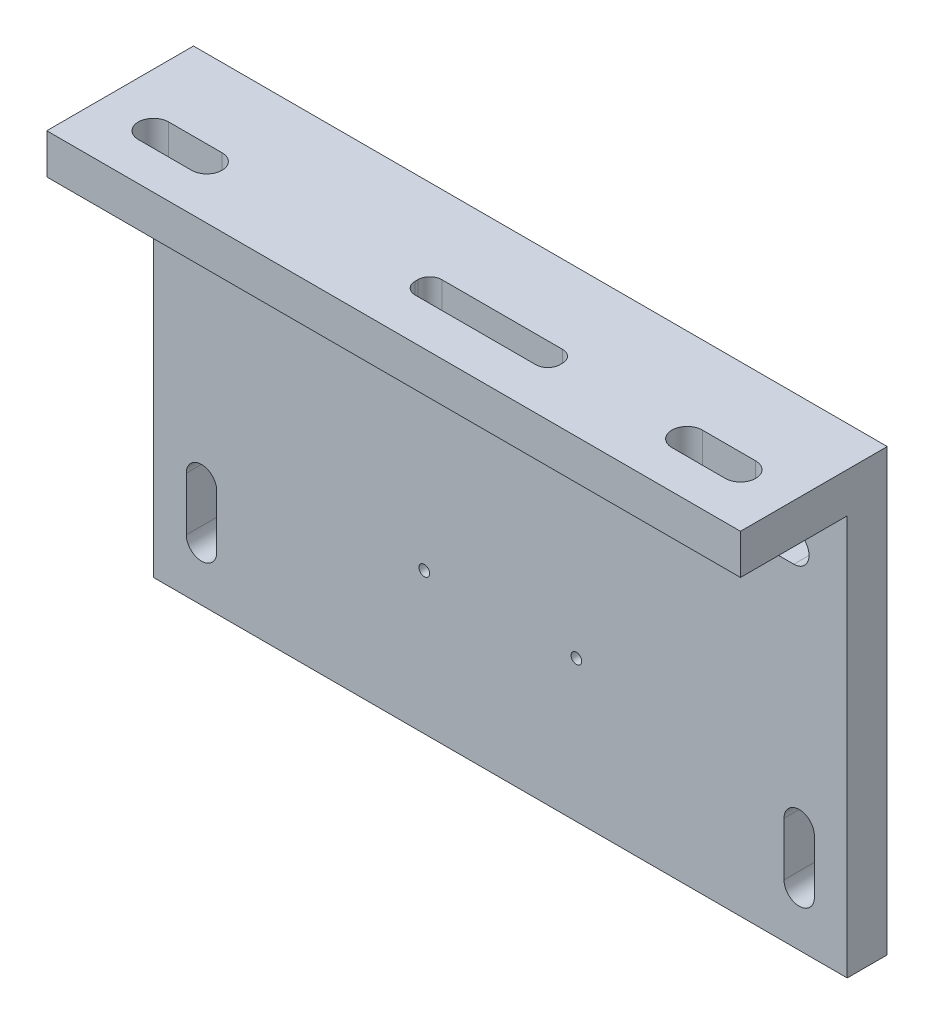
SolidWorks part; units mm, degrees
ref_plane "前视基准面" through (0, 0, 0) normal (0, 0, 1) x (1, 0, 0)
ref_plane "上视基准面" through (0, 0, 0) normal (0, 1, 0) x (1, 0, 0)
ref_plane "右视基准面" through (0, 0, 0) normal (1, 0, 0) x (0, 0, -1)
other "Configuration Table"
sketch "Skeleton" plane through (0, 0, 0) normal (0, 0, 1) x (1, 0, 0)
  line L0 (0, 170) -> (0, 0) construction
  point P0 (0, 0)
  point P1 (0, 170)
  dimension "D1" = 170
sketch "Sketch4" plane through (0, 0, 0) normal (1, 0, 0) x (0, 0, -1)
  line L1 (180, 170) -> (165, 170)
  line L2 (180, 170) -> (180, 20)
  line L3 (180, 20) -> (165, 20)
  line L4 (165, 170) -> (165, 20)
  dimension "D2" = 15
  dimension "D3" = 150
extrude "Middle" add sketch "Sketch4" along normal mid plane 260
sketch "Sketch10" plane through (0, 0, -180) normal (0, 0, -1) x (-1, 0, 0)
  line L0 (-130, 20) -> (130, 20) construction
  line L2 (0, -28.086) -> (0, 198.8498) construction
  line L3 (-130, 170) -> (130, 170) construction
  line L4 (-110, 155.7) -> (-90, 155.7)
  line L5 (-90, 144.3) -> (-110, 144.3)
  line L6 (90, 144.3) -> (110, 144.3)
  line L7 (110, 155.7) -> (90, 155.7)
  line L8 (-130, 20) -> (-130, 170) construction
  line L9 (-117.7, 60) -> (-117.7, 40)
  line L10 (-106.3, 40) -> (-106.3, 60)
  line L12 (106.3, 40) -> (106.3, 60)
  line L13 (117.7, 60) -> (117.7, 40)
  circle A0 centre (-28.5, 150) radius 2
  circle A1 centre (28.5, 150) radius 2
  circle A2 centre (28.5, 73) radius 2
  circle A3 centre (-28.5, 73) radius 2
  arc A4 (-90, 155.7) -> (-90, 144.3) centre (-90, 150) cw
  arc A5 (-110, 155.7) -> (-110, 144.3) centre (-110, 150) ccw
  arc A6 (90, 155.7) -> (90, 144.3) centre (90, 150) ccw
  arc A7 (110, 155.7) -> (110, 144.3) centre (110, 150) cw
  arc A8 (-117.7, 40) -> (-106.3, 40) centre (-112, 40) ccw
  arc A9 (-106.3, 60) -> (-117.7, 60) centre (-112, 60) ccw
  arc A10 (117.7, 40) -> (106.3, 40) centre (112, 40) cw
  arc A11 (106.3, 60) -> (117.7, 60) centre (112, 60) cw
  point P0 (-28.5, 150)
  point P1 (-28.5, 73)
  point P2 (28.5, 73)
  point P3 (28.5, 150)
  dimension "D4" = 4
  dimension "D5" = 4
  dimension "D6" = 4
  dimension "D7" = 4
  dimension "D12" = 11.4
  dimension "D1" = 77
  dimension "D2" = 77
  dimension "D3" = 57
  dimension "D8" = 20
  dimension "D9" = 11.4
  dimension "D10" = 20
  dimension "D11" = 20
  dimension "D13" = 18
  dimension "D14" = 20
  dimension "D15" = 20
extrude "Middle Holes" cut sketch "Sketch10" against normal through all
sketch "Sketch11" plane through (0, 0, 0) normal (1, 0, 0) x (0, 0, -1)
  line L1 (180, 170) -> (125, 170)
  line L2 (180, 170) -> (180, 185)
  line L3 (180, 185) -> (125, 185)
  line L4 (125, 170) -> (125, 185)
  dimension "D1" = 15
  dimension "D2" = 55
extrude "Upper" add sketch "Sketch11" along normal mid plane 260
sketch "Sketch12" plane through (0, 0, 0) normal (0, 1, 0) x (1, 0, 0)
  line L0 (-110, 139.3) -> (-90, 139.3)
  line L1 (-90, 150.7) -> (-110, 150.7)
  line L3 (130, 180) -> (-130, 180) construction
  line L4 (-130, 180) -> (-130, 125) construction
  line L5 (0, -99) -> (0, 99) construction
  line L6 (110, 139.3) -> (90, 139.3)
  line L7 (90, 150.7) -> (110, 150.7)
  arc A2 (-110, 150.7) -> (-110, 139.3) centre (-110, 145) ccw
  arc A3 (-90, 139.3) -> (-90, 150.7) centre (-90, 145) ccw
  arc A4 (90, 139.3) -> (90, 150.7) centre (90, 145) cw
  arc A5 (110, 150.7) -> (110, 139.3) centre (110, 145) cw
  dimension "D2" = 11.4
  dimension "D1" = 35
  dimension "D3" = 20
  dimension "D4" = 20
extrude "Upper Holes" cut sketch "Sketch12" against normal up to surface (15 mm away) from surface at 185 up to face at (0, 170, -145) starting at face at (0, 185, -152.5)
sketch "Sketch14" plane through (0, 185, 0) normal (0, 1, 0) x (1, 0, 0)
  line L0 (42.098, 145.2) -> (42.098, 146.2) construction
  line L1 (-7.6345, 140.7) -> (37.598, 140.7) construction
  line L15 (-12.1345, 146.2) -> (-12.1345, 145.2) construction
  line L16 (37.598, 150.7) -> (-7.6345, 150.7) construction
  line L17 (42.098, 145.2) -> (42.098, 146.2)
  line L18 (-7.6345, 140.7) -> (37.598, 140.7)
  line L19 (-12.1345, 146.2) -> (-12.1345, 145.2)
  line L20 (37.598, 150.7) -> (-7.6345, 150.7)
  arc A0 (37.598, 140.7) -> (42.098, 145.2) centre (37.598, 145.2) ccw construction
  arc A1 (42.098, 146.2) -> (37.598, 150.7) centre (37.598, 146.2) ccw construction
  arc A2 (-12.1345, 145.2) -> (-7.6345, 140.7) centre (-7.6345, 145.2) ccw construction
  arc A3 (-7.6345, 150.7) -> (-12.1345, 146.2) centre (-7.6345, 146.2) ccw construction
  arc A4 (37.598, 140.7) -> (42.098, 145.2) centre (37.598, 145.2) ccw
  arc A5 (42.098, 146.2) -> (37.598, 150.7) centre (37.598, 146.2) ccw
  arc A6 (-12.1345, 145.2) -> (-7.6345, 140.7) centre (-7.6345, 145.2) ccw
  arc A7 (-7.6345, 150.7) -> (-12.1345, 146.2) centre (-7.6345, 146.2) ccw
extrude "Cut-Extrude1" cut sketch "Sketch14" against normal through all
